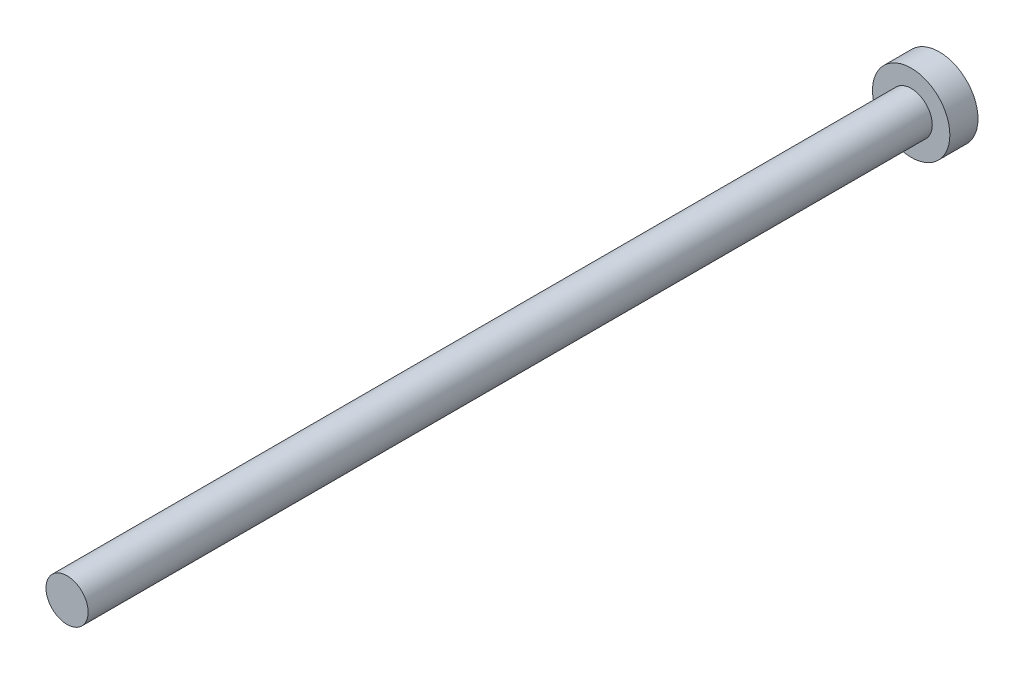
SolidWorks part; units mm, degrees
ref_plane "前视基准面" through (0, 0, 0) normal (0, 0, 1) x (1, 0, 0)
ref_plane "上视基准面" through (0, 0, 0) normal (0, 1, 0) x (1, 0, 0)
ref_plane "右视基准面" through (0, 0, 0) normal (1, 0, 0) x (0, 0, -1)
other "Configuration Table"
sketch "草图1" plane through (0, 0, 0) normal (0, 0, 1) x (1, 0, 0)
  circle A0 centre (0, 0) radius 1.5
extrude "M3x60光杆转轴简化" add sketch "草图1" along normal blind 60 from offset 26
sketch "草图2" plane through (0, 0, 0) normal (0, 0, 1) x (1, 0, 0)
  circle A0 centre (0, 0) radius 2.75
extrude "转轴螺钉头" add sketch "草图2" along normal blind 2 from offset 28
